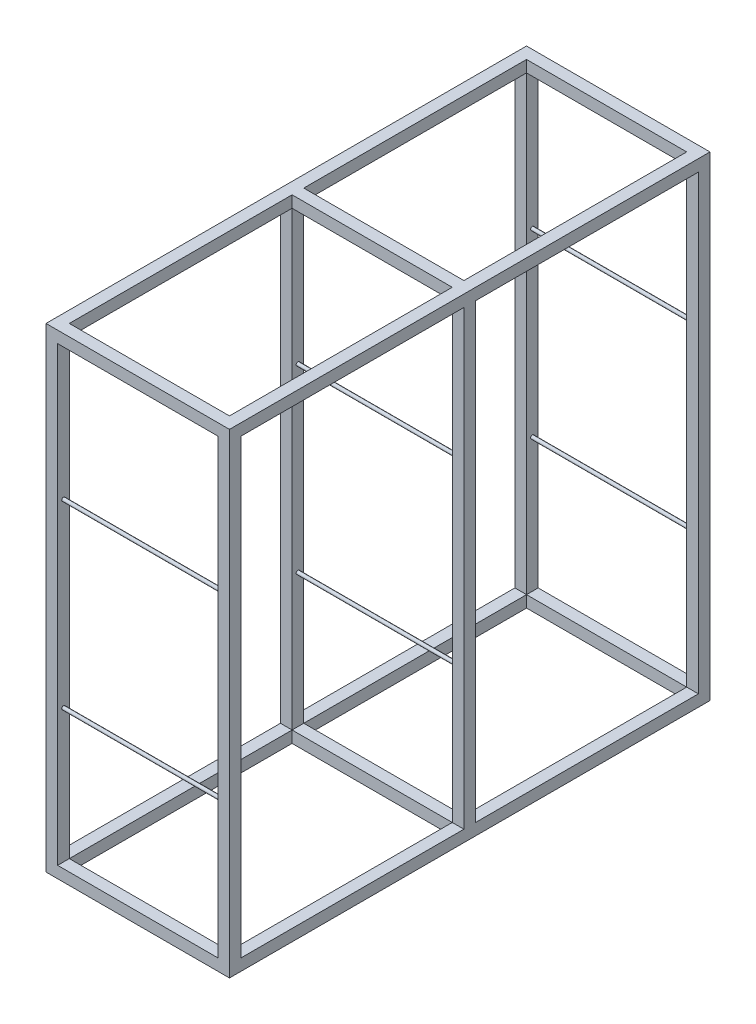
SolidWorks part; units mm, degrees
ref_plane "Front Plane" through (0, 0, 0) normal (0, 0, 1) x (1, 0, 0)
ref_plane "Top Plane" through (0, 0, 0) normal (0, 1, 0) x (1, 0, 0)
ref_plane "Right Plane" through (0, 0, 0) normal (1, 0, 0) x (0, 0, -1)
sketch "Sketch1" plane through (0, 0, 0) normal (0, 0, 1) x (1, 0, 0)
  line L0 (-313, 2) -> (-277, 2)
  line L1 (-315, 0) -> (-275, 0)
  line L2 (-315, 0) -> (-315, 40)
  line L3 (-315, 40) -> (-275, 40)
  line L4 (-275, 0) -> (-275, 40)
  line L5 (-277, 2) -> (-277, 38)
  line L6 (-313, 38) -> (-277, 38)
  line L7 (-313, 2) -> (-313, 38)
  line L8 (0, 0) -> (0, 157.1245) construction
  line L9 (313, 2) -> (313, 38)
  line L10 (313, 38) -> (277, 38)
  line L11 (277, 2) -> (277, 38)
  line L12 (275, 0) -> (275, 40)
  line L13 (315, 40) -> (275, 40)
  line L14 (315, 0) -> (315, 40)
  line L15 (315, 0) -> (275, 0)
  line L16 (313, 2) -> (277, 2)
  dimension "D1" = 40
  dimension "D2" = 40
  dimension "D4" = 2
extrude "Boss-Extrude1" add sketch "Sketch1" against normal mid plane 1650
sketch "Sketch2" plane through (-275, 0, 0) normal (1, 0, 0) x (0, 0, -1)
  line L0 (825, 0) -> (-825, 0) construction
  line L1 (-825, 40) -> (-785, 40)
  line L2 (-825, 40) -> (-825, 0)
  line L3 (-825, 0) -> (-785, 0)
  line L4 (-785, 40) -> (-785, 0)
  line L5 (-823, 38) -> (-787, 38)
  line L6 (-787, 38) -> (-787, 2)
  line L7 (-823, 2) -> (-787, 2)
  line L8 (-823, 38) -> (-823, 2)
  line L9 (0, 0) -> (0, 40) construction
  line L10 (825, 40) -> (-825, 40) construction
  line L11 (823, 38) -> (823, 2)
  line L12 (823, 2) -> (787, 2)
  line L13 (787, 38) -> (787, 2)
  line L14 (823, 38) -> (787, 38)
  line L15 (785, 40) -> (785, 0)
  line L16 (825, 0) -> (785, 0)
  line L17 (825, 40) -> (825, 0)
  line L18 (825, 40) -> (785, 40)
  line L19 (-18, 38) -> (18, 38)
  line L20 (-20, 40) -> (20, 40)
  line L21 (-20, 40) -> (-20, 0)
  line L22 (-20, 0) -> (20, 0)
  line L23 (20, 40) -> (20, 0)
  line L24 (18, 38) -> (18, 2)
  line L25 (-18, 2) -> (18, 2)
  line L26 (-18, 38) -> (-18, 2)
  dimension "D1" = 40
  dimension "D3" = 40
  dimension "D4" = 20
  dimension "D2" = 2
  dimension "D5" = 2
extrude "Boss-Extrude2" add sketch "Sketch2" along normal up to surface (550 mm away) up to face at (275, 20, 0)
sketch "Sketch3" plane through (0, 40, 0) normal (0, 1, 0) x (1, 0, 0)
  line L0 (275, -20) -> (275, -785) construction
  line L1 (-315, -825) -> (-275, -825)
  line L2 (-315, -825) -> (-315, -785)
  line L3 (-315, -785) -> (-275, -785)
  line L4 (-275, -825) -> (-275, -785)
  line L5 (315, -825) -> (275, -825)
  line L6 (315, -825) -> (315, -785)
  line L7 (315, -785) -> (275, -785)
  line L8 (275, -825) -> (275, -785)
  line L9 (275, -785) -> (-275, -785) construction
  line L10 (315, 825) -> (315, -825) construction
  line L11 (275, -20) -> (315, -20)
  line L12 (275, -20) -> (275, 20)
  line L13 (275, 20) -> (315, 20)
  line L14 (315, -20) -> (315, 20)
  line L15 (-315, 825) -> (-315, -825) construction
  line L16 (-275, -20) -> (-315, -20)
  line L17 (-275, -20) -> (-275, 20)
  line L18 (-275, 20) -> (-315, 20)
  line L19 (-315, -20) -> (-315, 20)
  line L20 (275, 20) -> (-275, 20) construction
  line L21 (-315, 825) -> (-275, 825)
  line L22 (-315, 825) -> (-315, 785)
  line L23 (-315, 785) -> (-275, 785)
  line L24 (-275, 825) -> (-275, 785)
  line L25 (275, 785) -> (315, 785)
  line L26 (275, 785) -> (275, 825)
  line L27 (275, 825) -> (315, 825)
  line L28 (315, 785) -> (315, 825)
  line L29 (313, -823) -> (277, -823)
  line L30 (277, -823) -> (277, -787)
  line L31 (313, -787) -> (277, -787)
  line L32 (313, -823) -> (313, -787)
  line L33 (-313, -823) -> (-277, -823)
  line L34 (-277, -823) -> (-277, -787)
  line L35 (-313, -787) -> (-277, -787)
  line L36 (-313, -823) -> (-313, -787)
  line L37 (-277, -18) -> (-313, -18)
  line L38 (-313, -18) -> (-313, 18)
  line L39 (-277, 18) -> (-313, 18)
  line L40 (-277, -18) -> (-277, 18)
  line L41 (277, -18) -> (313, -18)
  line L42 (313, -18) -> (313, 18)
  line L43 (277, 18) -> (313, 18)
  line L44 (277, -18) -> (277, 18)
  line L45 (277, 787) -> (313, 787)
  line L46 (313, 787) -> (313, 823)
  line L47 (277, 823) -> (313, 823)
  line L48 (277, 787) -> (277, 823)
  line L49 (-313, 823) -> (-277, 823)
  line L50 (-277, 823) -> (-277, 787)
  line L51 (-313, 787) -> (-277, 787)
  line L52 (-313, 823) -> (-313, 787)
  dimension "D1" = 0
  dimension "D2" = 0
  dimension "D3" = 2
  dimension "D4" = 2
  dimension "D5" = 2
  dimension "D6" = 2
  dimension "D7" = 2
  dimension "D8" = 2
extrude "Boss-Extrude5" add sketch "Sketch3" along normal blind 1551.5
sketch "Sketch5" plane through (0, 0, 825) normal (0, 0, 1) x (1, 0, 0)
  line L0 (-314, 1592.5) -> (-276, 1592.5)
  line L1 (-315, 1591.5) -> (-275, 1591.5)
  line L2 (-315, 1591.5) -> (-315, 1631.5)
  line L3 (-315, 1631.5) -> (-275, 1631.5)
  line L4 (-275, 1591.5) -> (-275, 1631.5)
  line L5 (-276, 1592.5) -> (-276, 1630.5)
  line L6 (-314, 1630.5) -> (-276, 1630.5)
  line L7 (-314, 1592.5) -> (-314, 1630.5)
  line L8 (-275, 1569.7537) -> (275, 1569.7537) construction
  line L9 (-275, 1591.5) -> (-275, 40) construction
  line L10 (275, 1591.5) -> (275, 40) construction
  line L11 (0, 1569.7537) -> (0, 1600.3529) construction
  line L12 (314, 1592.5) -> (314, 1630.5)
  line L13 (314, 1630.5) -> (276, 1630.5)
  line L14 (276, 1592.5) -> (276, 1630.5)
  line L15 (275, 1591.5) -> (275, 1631.5)
  line L16 (315, 1631.5) -> (275, 1631.5)
  line L17 (315, 1591.5) -> (315, 1631.5)
  line L18 (315, 1591.5) -> (275, 1591.5)
  line L19 (314, 1592.5) -> (276, 1592.5)
  dimension "D1" = 40
  dimension "D2" = 40
  dimension "D3" = 1
extrude "Boss-Extrude6" add sketch "Sketch5" against normal up to surface (1650 mm away) up to face at (-295, 20, -825)
sketch "Sketch6" plane through (-275, 0, 0) normal (1, 0, 0) x (0, 0, -1)
  line L0 (825, 1631.5) -> (-825, 1631.5) construction
  line L1 (-20, 1591.5) -> (20, 1591.5)
  line L2 (-20, 1591.5) -> (-20, 1631.5)
  line L3 (-20, 1631.5) -> (20, 1631.5)
  line L4 (20, 1591.5) -> (20, 1631.5)
  line L5 (-19, 1592.5) -> (19, 1592.5)
  line L6 (-785, 1591.5) -> (-825, 1591.5)
  line L7 (-785, 1591.5) -> (-785, 1631.5)
  line L8 (-785, 1631.5) -> (-825, 1631.5)
  line L9 (-825, 1591.5) -> (-825, 1631.5)
  line L10 (785, 1591.5) -> (825, 1591.5)
  line L11 (785, 1591.5) -> (785, 1631.5)
  line L12 (785, 1631.5) -> (825, 1631.5)
  line L13 (825, 1591.5) -> (825, 1631.5)
  line L14 (19, 1592.5) -> (19, 1630.5)
  line L15 (-19, 1630.5) -> (19, 1630.5)
  line L16 (-19, 1592.5) -> (-19, 1630.5)
  line L17 (786, 1592.5) -> (824, 1592.5)
  line L18 (824, 1592.5) -> (824, 1630.5)
  line L19 (786, 1630.5) -> (824, 1630.5)
  line L20 (786, 1592.5) -> (786, 1630.5)
  line L21 (-786, 1592.5) -> (-824, 1592.5)
  line L22 (-824, 1592.5) -> (-824, 1630.5)
  line L23 (-786, 1630.5) -> (-824, 1630.5)
  line L24 (-786, 1592.5) -> (-786, 1630.5)
  dimension "D1" = 40
  dimension "D2" = 1
  dimension "D3" = 1
  dimension "D4" = 1
extrude "Boss-Extrude7" add sketch "Sketch6" along normal up to surface (550 mm away) up to face at (275, 822.4167, 0)
sketch "Sketch7" plane through (275, 0, 0) normal (-1, 0, 0) x (0, 0, 1)
  line L0 (0, 1119) -> (0, 1001.9302) construction
  line L1 (805, 13.123) -> (805, 1555.6936) construction
  line L4 (825, 1631.5) -> (825, 0) construction
  line L7 (-825, 1125) -> (825, 1125) construction
  circle A0 centre (805, 1119) radius 6
  circle A1 centre (805, 499) radius 6
  circle A2 centre (0, 1119) radius 6
  circle A3 centre (0, 499) radius 6
  circle A4 centre (-805, 499) radius 6
  circle A5 centre (-805, 1119) radius 6
  dimension "D1" = 12
  dimension "D3" = 6
  dimension "D2" = 12
  dimension "D4" = 12
  dimension "D5" = 12
  dimension "D6" = 20
extrude "Boss-Extrude8" add sketch "Sketch7" along normal up to surface (550 mm away) contours A0 | A1 | A2 | A3 | A4 | A5 up to face at (-275, 1611.5, 0)
sketch "Sketch8" plane through (0, 0, 825) normal (0, 0, 1) x (1, 0, 0)
  line L2 (-315, 1631.5) -> (-275, 1631.5)
  line L3 (-315, 1631.5) -> (-315, 1591.5)
  line L4 (-315, 1591.5) -> (-275, 1591.5)
  line L5 (-275, 1631.5) -> (-275, 1591.5)
  line L6 (275, 1591.5) -> (315, 1591.5)
  line L7 (275, 1591.5) -> (275, 1631.5)
  line L8 (275, 1631.5) -> (315, 1631.5)
  line L9 (315, 1591.5) -> (315, 1631.5)
  line L10 (-315, 0) -> (-275, 0)
  line L11 (-315, 0) -> (-315, 40)
  line L12 (-315, 40) -> (-275, 40)
  line L13 (-275, 0) -> (-275, 40)
  line L14 (275, 40) -> (315, 40)
  line L15 (275, 40) -> (275, 0)
  line L16 (275, 0) -> (315, 0)
  line L18 (315, 40) -> (315, 0)
extrude "Boss-Extrude10" add sketch "Sketch8" against normal blind 1
sketch "Sketch9" plane through (0, 0, -825) normal (0, 0, -1) x (-1, 0, 0)
  line L1 (-315, 1631.5) -> (-275, 1631.5)
  line L2 (-315, 1631.5) -> (-315, 1591.5)
  line L3 (-315, 1591.5) -> (-275, 1591.5)
  line L4 (-275, 1631.5) -> (-275, 1591.5)
  line L5 (275, 1591.5) -> (315, 1591.5)
  line L6 (275, 1591.5) -> (275, 1631.5)
  line L7 (275, 1631.5) -> (315, 1631.5)
  line L8 (315, 1591.5) -> (315, 1631.5)
  line L9 (275, 40) -> (315, 40)
  line L10 (275, 40) -> (275, 0)
  line L11 (275, 0) -> (315, 0)
  line L12 (315, 40) -> (315, 0)
  line L13 (-315, 0) -> (-275, 0)
  line L14 (-315, 0) -> (-315, 40)
  line L15 (-315, 40) -> (-275, 40)
  line L16 (-275, 0) -> (-275, 40)
extrude "Boss-Extrude11" add sketch "Sketch9" against normal blind 1
